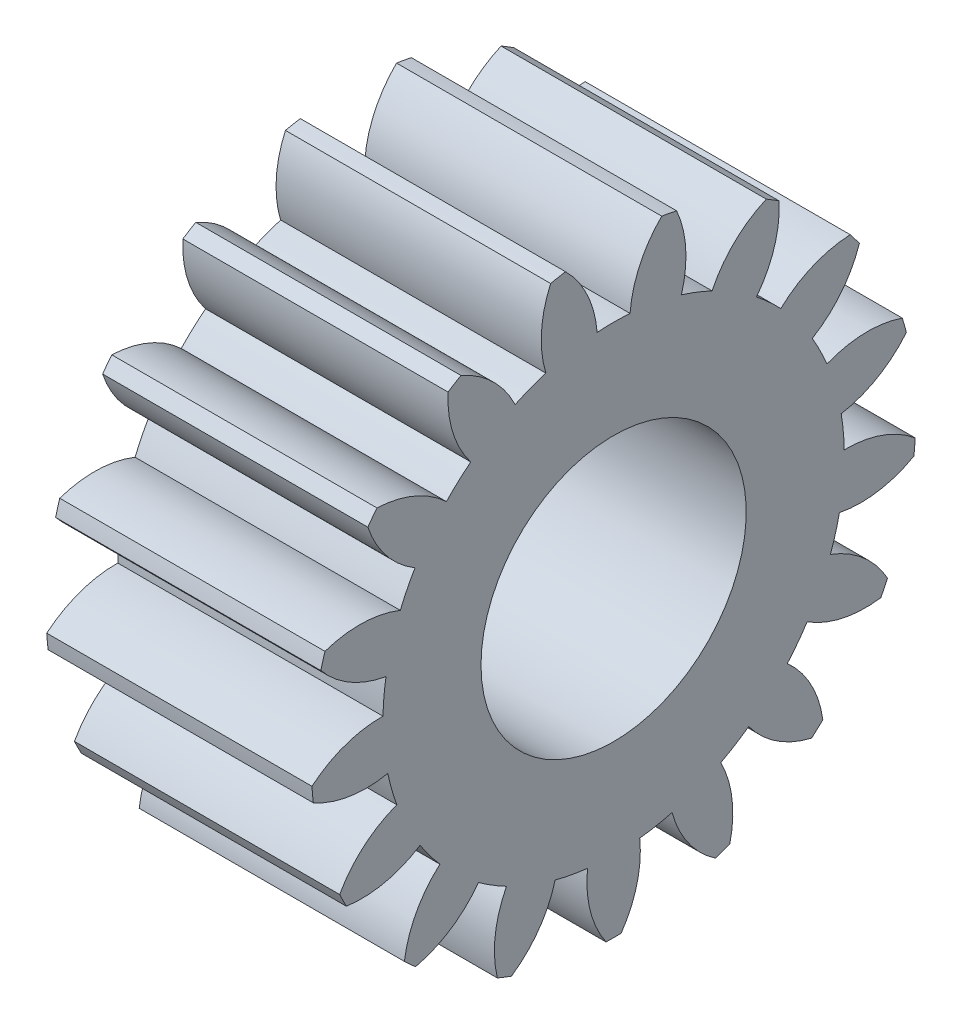
SolidWorks part; units mm, degrees
ref_plane "Plane1" through (0, 0, 0) normal (0, 0, 1) x (1, 0, 0)
ref_plane "Plane2" through (0, 0, 0) normal (0, 1, 0) x (1, 0, 0)
ref_plane "Plane3" through (0, 0, 0) normal (1, 0, 0) x (0, 0, -1)
other "Configuration Table"
sketch "HoldingSke" plane through (0, 0, 0) normal (0, 1, 0) x (1, 0, 0)
  line L0 (0, 0) -> (1.5938, -0.4873)
  line L1 (-15, 0) -> (100, 0) construction
  line L2 (0, 0) -> (-2.1039, 2.3779)
  line L3 (0, 0) -> (-11.863, 4.5341)
  line L4 (0, 0) -> (8.2586, 2.5249)
  line L5 (0, 0) -> (-46.8476, -17.4728)
  line L6 (0, 0) -> (-4.1448, -2.7965)
  line L7 (-2.1039, 2.3779) -> (8.6586, 51.2059)
  line L8 (-76.2, 54.61) -> (-75.3, 54.61)
  line L9 (-71.009, 38.7566) -> (-53.1078, 45.2721)
  line L10 (-76.2, 71.12) -> (104.1128, 71.12)
  line L11 (0, 0) -> (-5, 0)
  line L12 (-76.2, 101.6) -> (-76.177, 101.6)
  line L13 (24.9733, 27.94) -> (52.9518, 28.4284)
  line L14 (24.9733, 27.94) -> (24.9743, 27.94)
  line L15 (24.9733, 27.94) -> (100.4006, 29.5858)
  line L16 (-63.627, -0.6) -> (-12.827, -0.6)
  circle A0 centre (0, 0) radius 2.5
  circle A1 centre (0, 0) radius 4.349
  circle A2 centre (0, 0) radius 37.5
  circle A3 centre (0, 0) radius 2.5
  dimension "MHD" = 8.698
  dimension "Hub_dia" = 75
  dimension "Bore" = 5
  dimension "MBD" = 5
  dimension "Num_teeth" = 17
  dimension "Pitch" = 1.6667
  dimension "Overall_len" = 50
  dimension "Show_teeth" = 17
  dimension "Thickness" = 5
  dimension "OAL" = 50.0001
  dimension "T_dim" = 0.9
  dimension "Ap" = 20
  dimension "H" = 19.05
  dimension "Pitch_radius" = 180.3128
  dimension "Width" = 5
  dimension "Backlash" = 0.023
  dimension "Addendum_fac" = 1
  dimension "Dedendum_fac" = 1.25
  dimension "Clearance_fac" = 0.25
  dimension "Dedendum_add" = 0.001
  dimension "Module" = 0.6
sketch "BasProSke" plane through (0, 0, 0) normal (0, 1, 0) x (1, 0, 0)
  line L0 (-10, 0) -> (60, 0) construction
  line L1 (0, 0) -> (0, 5.7)
  line L2 (0, 0) -> (5, 0)
  line L3 (5, 0) -> (5, 5.7)
  line L4 (5, 5.7) -> (0, 5.7)
  dimension "Thickness" = 5
  dimension "Diameter" = 11.4
revolve "Base-Revolve" add sketch "BasProSke" angle 360 about L0
sketch "TooCutSke" plane through (0, 0, 0) normal (1, 0, 0) x (0, 0, -1)
  line L1 (0, 0) -> (0, 107) construction
  line L2 (0, 0) -> (-0.5108, 5.0744) construction
  line L3 (0, 0) -> (-1.8676, 9.9906) construction
  line L4 (-0.5108, 5.0744) -> (-0.9338, 4.9953) construction
  arc A0 (0.3104, 4.3379) -> (-0.3104, 4.3379) centre (0, 0) ccw
  arc A1 (0.9293, 5.6495) -> (-0.9293, 5.6495) centre (0, 0) ccw
  circle A2 centre (0, 0) radius 5.1 construction
  circle A3 centre (0, 0) radius 4.7924 construction
  arc A4 (-0.3104, 4.3379) -> (-0.9293, 5.6495) centre (-2.3443, 4.1799) ccw
  arc A5 (0.9293, 5.6495) -> (0.3104, 4.3379) centre (2.3443, 4.1799) ccw
  dimension "Root_dia" = 8.698
  dimension "Overcut_dia" = 11.4508
  dimension "Pitch_dia" = 10.2
  dimension "Base_dia" = 9.5849
  dimension "Flank_rad" = 2.04
  dimension "Half_ang" = 10.588
  dimension "Half_CT" = 0.4303
extrude "ToothCut" cut sketch "TooCutSke" along normal through all
fillet "Breaks" [suppressed] radius 0.012
fillet "RootFillets" [suppressed] radius 0.151
pattern_circular "TeethCuts" count 17 every 21.176 about axis through (-10, 0, 0) along (1, 0, 0) of "ToothCut", "RootFillets", "Breaks"
sketch "HubNeaOneSke" plane through (0, 0, 0) normal (-1, 0, 0) x (0, 0, 1)
  circle A0 centre (0, 0) radius 4.349
  dimension "Diameter" = 8.698
extrude "HubNearOne" [suppressed] add sketch "HubNeaOneSke" along normal blind 45.0001
sketch "HubNeaBotSke" plane through (0, 0, 0) normal (-1, 0, 0) x (0, 0, 1)
  circle A0 centre (0, 0) radius 4.349
  dimension "Diameter" = 8.698
extrude "HubNearBoth" [suppressed] add sketch "HubNeaBotSke" along normal blind 22.5
ref_plane "FarPln" through (5, 0, 0) normal (1, 0, 0) x (0, 0, -1)
sketch "HubFarSke" plane through (5, 0, 0) normal (1, 0, 0) x (0, 0, -1)
  circle A0 centre (0, 0) radius 4.349
  dimension "Diameter" = 8.698
extrude "HubFar" [suppressed] add sketch "HubFarSke" along normal blind 22.5
sketch "BorSke" plane through (0, 0, 0) normal (1, 0, 0) x (0, 0, -1)
  circle A0 centre (0, 0) radius 2.5
  dimension "Diameter" = 5
extrude "Bore" cut sketch "BorSke" along normal mid plane 100.0001
sketch "KeySke" plane through (0, 0, 0) normal (1, 0, 0) x (0, 0, -1)
  line L0 (-1, 0) -> (-1, 3.4)
  line L1 (-1, 3.4) -> (1, 3.4)
  line L2 (1, 3.4) -> (1, 0)
  line L3 (0, 0) -> (0, 34) construction
  line L4 (-1, 0) -> (1, 0)
  dimension "Offset" = 3.4
  dimension "Width" = 2
extrude "Keyway" [suppressed] cut sketch "KeySke" along normal mid plane 100.0001
pattern_circular "Keyway2" [suppressed] count 2 every 90 about axis through (-10, 0, 0) along (1, 0, 0)
equation "' \"Module@HoldingSke\" = 6.35"
equation "' \"Num_teeth@HoldingSke\" = 12"
equation "' \"Ap@HoldingSke\" =  20"
equation "' \"Ap@HoldingSke\" = 20"
equation "' \"Width@HoldingSke\" = 0.5 * 25.4"
equation "' \"Hub_dia@HoldingSke\"= 1 * 25.4"
equation "' \"Hub_dia@HoldingSke\" = 1 * 25.4"
equation "' \"Overall_len@HoldingSke\" = 1.0 * 25.4"
equation "' \"Bore@HoldingSke\" = 0.75 * 25.4"
equation "' \"T_dim@HoldingSke\" = 0.1 * 25.4"
equation "' \"Width@KeySke\" = 0.25 * 25.4"
equation "' \"Show_teeth@HoldingSke\" = 13"
equation "' \"Backlash@HoldingSke\" = 0.009 * 25.4"
equation "' \"Addendum_fac@HoldingSke\" = 1.0"
equation "' \"Dedendum_fac@HoldingSke\" = 1.25"
equation "' \"Dedendum_add@HoldingSke\" = 0.00005 * 25.4"
equation "' \"Clearance_fac@HoldingSke\" = 0.25"
equation "\"Pitch@HoldingSke\" = 1 / \"Module@HoldingSke\""
equation "\"Overcut_dia@TooCutSke\" = (\"Num_teeth@HoldingSke\" + 2 * \"Addendum_fac@HoldingSke\") / \"Pitch@HoldingSke\" + 0.002 * 25.4"
equation "\"Pitch_dia@TooCutSke\" = \"Num_teeth@HoldingSke\" / \"Pitch@HoldingSke\""
equation "\"Base_dia@TooCutSke\" = \"Num_teeth@HoldingSke\" / \"Pitch@HoldingSke\" * cos((\"Ap@HoldingSke\"  * 3.14159265 / 180))"
equation "\"Root_dia@TooCutSke\" = (\"Num_teeth@HoldingSke\" + 2) / \"Pitch@HoldingSke\" - 2 * (\"Addendum_fac@HoldingSke\" + \"Dedendum_fac@HoldingSke\") / \"Pitch@HoldingSke\" - \"Dedendum_add@HoldingSke\" * 2"
equation "\"Half_ang@TooCutSke\" = 180 / \"Num_teeth@HoldingSke\""
equation "\"Half_CT@TooCutSke\" = \"Num_teeth@HoldingSke\" / \"Pitch@HoldingSke\" * sin((3.14159265 / 2 / \"Num_teeth@HoldingSke\")) / 2 - 7 * \"Backlash@HoldingSke\" / 4"
equation "\"Flank_rad@TooCutSke\" = \"Num_teeth@HoldingSke\" / \"Pitch@HoldingSke\" / 5"
equation "\"Radius@RootFillets\" = \"Clearance_fac@HoldingSke\" / \"Pitch@HoldingSke\" + \"Dedendum_add@HoldingSke\""
equation "\"Break_rad@Breaks\" = 0.02 / \"Pitch@HoldingSke\""
equation "\"Thickness@HoldingSke\" = \"Width@HoldingSke\""
equation "\"OAL@HoldingSke\" = \"Thickness@HoldingSke\""
equation "\"MHD@HoldingSke\" = (\"Num_teeth@HoldingSke\" + 2) / \"Pitch@HoldingSke\" - 2 * (\"Addendum_fac@HoldingSke\" + \"Dedendum_fac@HoldingSke\")  / \"Pitch@HoldingSke\" - \"Dedendum_add@HoldingSke\" * 2"
equation "\"MBD@HoldingSke\" = (\"Num_teeth@HoldingSke\" + 2) / \"Pitch@HoldingSke\" - 2 * (\"Addendum_fac@HoldingSke\" + \"Dedendum_fac@HoldingSke\")  / \"Pitch@HoldingSke\" - \"Dedendum_add@HoldingSke\" * 2 - 0.002 * 25.4"
equation "\"MHD@HoldingSke\" = ((sgn( \"MHD@HoldingSke\" - \"Hub_dia@HoldingSke\" )-1)*( \"MHD@HoldingSke\" - \"Hub_dia@HoldingSke\" ))/-2+ \"Hub_dia@HoldingSke\""
equation "\"MBD@HoldingSke\" = ((sgn( \"MBD@HoldingSke\" - \"Bore@HoldingSke\" )-1)*( \"MBD@HoldingSke\" - \"Bore@HoldingSke\" ))/-2+ \"Bore@HoldingSke\""
equation "\"OAL@HoldingSke\" = ((sgn( \"OAL@HoldingSke\" - \"Overall_len@HoldingSke\" )+1)*( \"OAL@HoldingSke\" - \"Overall_len@HoldingSke\" ))/2 + \"Overall_len@HoldingSke\" + 0.000002 * 25.4"
equation "\"Num_teeth@TeethCuts\" = int( \"Show_teeth@HoldingSke\" ) + 1"
equation "\"Num_teeth@TeethCuts\" = ((sgn( \"Num_teeth@TeethCuts\" - \"Num_teeth@HoldingSke\" )-1)*( \"Num_teeth@TeethCuts\" - \"Num_teeth@HoldingSke\" ))/-2+ \"Num_teeth@HoldingSke\""
equation "\"Num_teeth@TeethCuts\" = ((sgn( \"Num_teeth@TeethCuts\" - 2.0)+1)*( \"Num_teeth@TeethCuts\" - 2.0))/2 +2.0"
equation "\"Angle@TeethCuts\" = 360.0 / \"Num_teeth@HoldingSke\""
equation "\"Diameter@BasProSke\" = (\"Num_teeth@HoldingSke\" + 2 * \"Addendum_fac@HoldingSke\") / \"Pitch@HoldingSke\""
equation "\"Thickness@BasProSke\"  = \"Thickness@HoldingSke\""
equation "' \"Fillet_rad@BasProSke\" =  \"Thickness@HoldingSke\" * 0.05"
equation "' \"Fillet_rad@BasProSke\" = \"Thickness@HoldingSke\" * 0.05"
equation "\"MHD@HoldingSke\" = ((sgn( \"MHD@HoldingSke\" - \"Root_dia@TooCutSke\" )-1)*( \"MHD@HoldingSke\" - \"Root_dia@TooCutSke\" ))/-2+ \"Root_dia@TooCutSke\""
equation "\"Diameter@HubNeaOneSke\" = \"MHD@HoldingSke\""
equation "\"Length@HubNearOne\" = \"OAL@HoldingSke\" - \"Thickness@BasProSke\""
equation "\"Diameter@HubNeaBotSke\" = \"MHD@HoldingSke\""
equation "\"Length@HubNearBoth\" = ( \"OAL@HoldingSke\" - \"Thickness@BasProSke\" ) / 2.0"
equation "\"Thickness@FarPln\" = \"Thickness@BasProSke\""
equation "\"Diameter@HubFarSke\" = \"MHD@HoldingSke\""
equation "\"Length@HubFar\" = ( \"OAL@HoldingSke\" - \"Thickness@BasProSke\" ) / 2.0"
equation "\"Diameter@BorSke\" = \"MBD@HoldingSke\""
equation "\"D1@Bore\" = \"OAL@HoldingSke\" * 2.0"
equation "\"D1@Keyway\" = \"OAL@HoldingSke\" * 2.0"
equation "\"Offset@KeySke\" = \"T_dim@HoldingSke\" + \"MBD@HoldingSke\" / 2.0"
